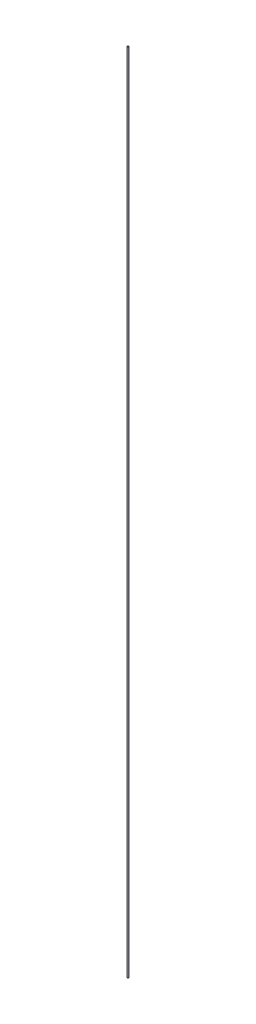
SolidWorks part; units mm, degrees
ref_plane "Front Plane" through (0, 0, 0) normal (0, 0, 1) x (1, 0, 0)
ref_plane "Top Plane" through (0, 0, 0) normal (0, 1, 0) x (1, 0, 0)
ref_plane "Right Plane" through (0, 0, 0) normal (1, 0, 0) x (0, 0, -1)
sketch "Sketch1" plane through (0, 0, 0) normal (0, 0, 1) x (1, 0, 0)
  line L0 (0, 0) -> (0, 8304.784)
  dimension "D1" = 8304.784
sweep "Sweep1" add path "Sketch1" circular profile diameter 12.7 parameters "D3"=12.7
